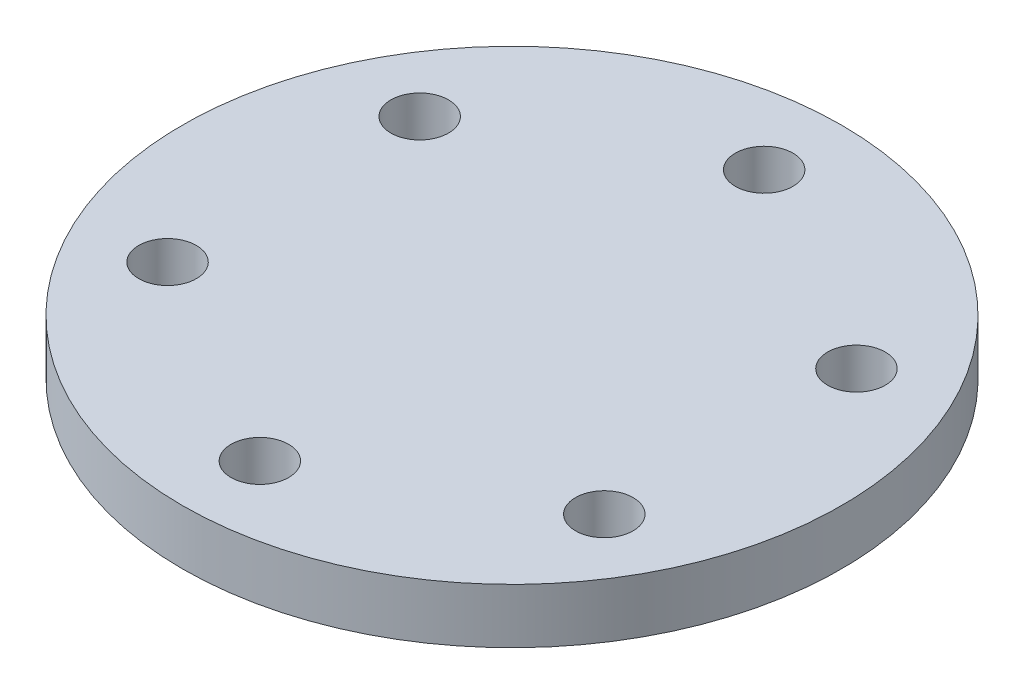
SolidWorks part; units mm, degrees
ref_plane "Front Plane" through (0, 0, 0) normal (0, 0, 1) x (1, 0, 0)
ref_plane "Top Plane" through (0, 0, 0) normal (0, 1, 0) x (1, 0, 0)
ref_plane "Right Plane" through (0, 0, 0) normal (1, 0, 0) x (0, 0, -1)
sketch "Sketch1" plane through (0, 0, 0) normal (0, 1, 0) x (1, 0, 0)
  circle A0 centre (0, 0) radius 60.0888
extrude "Boss-Extrude1" add sketch "Sketch1" along normal blind 10
sketch "Sketch2" plane through (0, 0, 0) normal (0, 1, 0) x (1, 0, 0)
  circle A1 centre (0, 45.977) radius 5.2551
extrude "Cut-Extrude1" cut sketch "Sketch2" along normal blind 10
pattern_circular "CirPattern1" count 6 over 360 about axis through (0, 0, 0) along (0, 1, 0) of "Cut-Extrude1"
